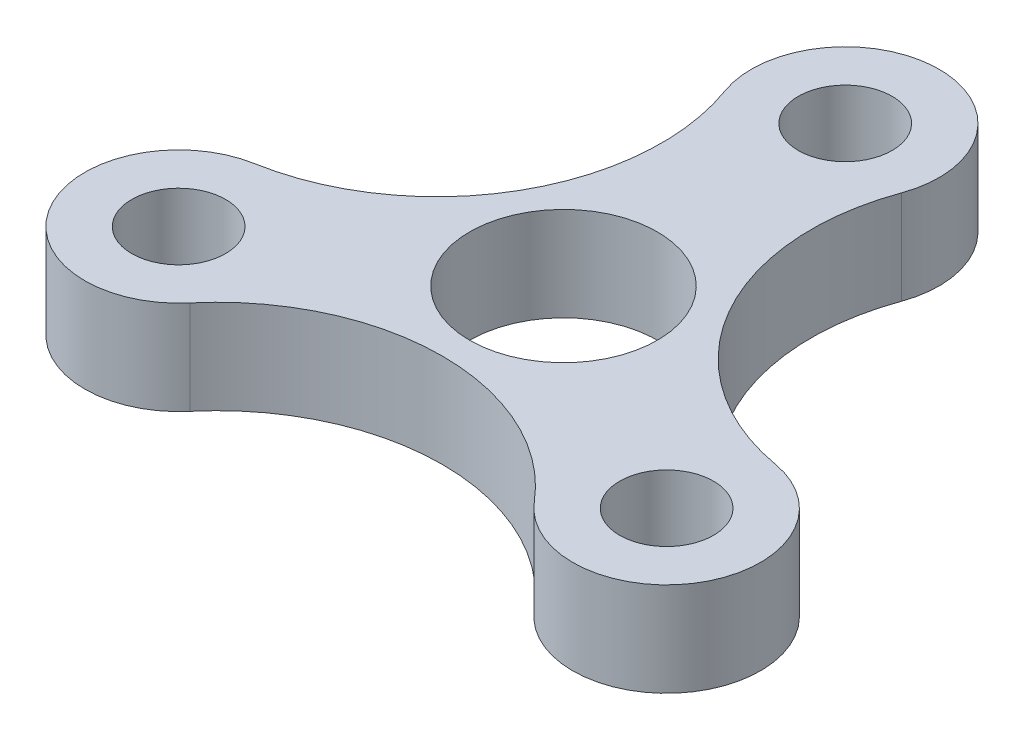
SolidWorks part; units mm, degrees
ref_plane "Front Plane" through (0, 0, 0) normal (0, 0, 1) x (1, 0, 0)
ref_plane "Top Plane" through (0, 0, 0) normal (0, 1, 0) x (1, 0, 0)
ref_plane "Right Plane" through (0, 0, 0) normal (1, 0, 0) x (0, 0, -1)
sketch "Sketch1" plane through (0, 0, 0) normal (0, 1, 0) x (1, 0, 0)
  line L0 (0, 0) -> (-19755.4178, 0)
  line L1 (0, 0) -> (0, 19755.4178)
  circle A0 centre (0, 0) radius 10
  circle A1 centre (0, 0) radius 30 construction
  circle A2 centre (0, 30) radius 5
  circle A3 centre (0, 30) radius 10
  circle A4 centre (25.9808, -15) radius 10
  circle A6 centre (-25.9808, -15) radius 10
  circle A8 centre (25.9808, -15) radius 5
  circle A9 centre (-25.9808, -15) radius 5
  arc A10 (-27.7276, -5.1537) -> (-9.4005, 26.5897) centre (-31.9104, 18.4235) ccw
  circle A11 centre (0, 0) radius 30 [skipped]
  circle A12 centre (0, 0) radius 30 [skipped]
  arc A13 (9.4005, 26.5897) -> (27.7276, -5.1537) centre (31.9104, 18.4235) ccw
  arc A14 (18.3271, -21.4359) -> (-18.3271, -21.4359) centre (0, -36.8469) ccw
  point P19 (0, 0)
  point P24 (0, 0)
  point P25 (0, 0)
  point P34 (0, 0)
  dimension "D1" = 20
  dimension "D2" = 60
  dimension "D3" = 10
  dimension "D4" = 20
  dimension "D5" = 3
  dimension "D6" = 3
  dimension "D7" = 3
extrude "Boss-Extrude1" add sketch "Sketch1" along normal blind 10 contours A10 L0 A0 L1 A3 | A14 L1 A0 L0 A10 A6 | A6 A9 | A4 A8 | L1 A3 A2 | L1 A3 A2 | A14 A4 A13 L0 A0 L1 | A13 A3 L1 A0 L0
